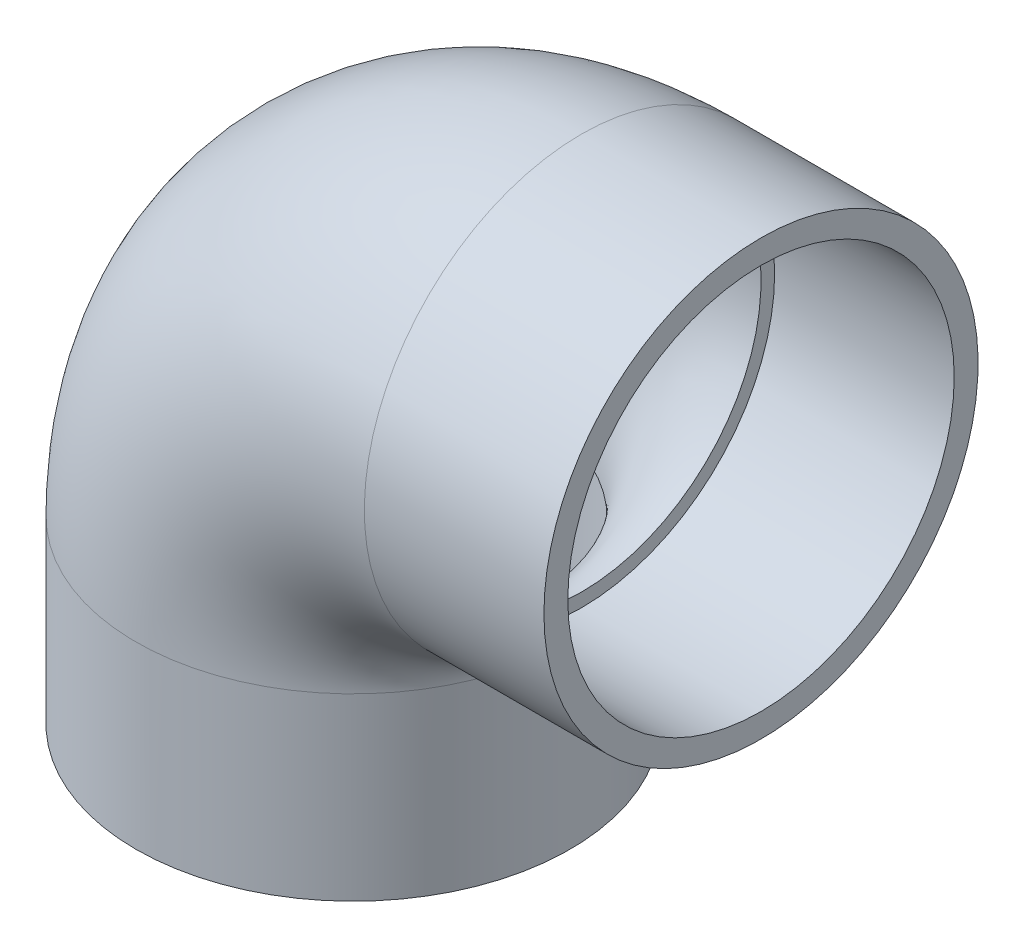
SolidWorks part; units mm, degrees
ref_plane "Alzado" through (0, 0, 0) normal (0, 0, 1) x (1, 0, 0)
ref_plane "Planta" through (0, 0, 0) normal (0, 1, 0) x (1, 0, 0)
ref_plane "Vista lateral" through (0, 0, 0) normal (1, 0, 0) x (0, 0, -1)
sketch "Croquis3" plane through (0, 0, 0) normal (0, 0, 1) x (1, 0, 0)
  line L0 (0, 79) -> (0, 0)
  line L1 (100.5, 179.5) -> (179.5, 179.5)
  arc A0 (0, 79) -> (100.5, 179.5) centre (100.5, 79) cw
  dimension "D1" = 100.5
  dimension "D2" = 79
  dimension "D3" = 79
sketch "Croquis4" plane through (0, 0, 0) normal (0, 1, 0) x (1, 0, 0)
  circle A0 centre (0, 0) radius 95.5
  circle A1 centre (0, 0) radius 79
  dimension "D1" = 191
  dimension "D2" = 158
sweep "Barrer5" add profiles "Croquis4" path "Croquis3"
sketch "Croquis6" plane through (0, 0, 0) normal (0, -1, 0) x (1, 0, 0)
  circle A0 centre (0, 0) radius 79
  circle A1 centre (0, 0) radius 85
  dimension "D1" = 158
  dimension "D2" = 170
extrude "Cortar-Extruir1" cut sketch "Croquis6" against normal blind 79
sketch "Croquis7" plane through (179.5, 0, 0) normal (1, 0, 0) x (0, 0, -1)
  circle A0 centre (0, 179.5) radius 79
  circle A1 centre (0, 179.5) radius 85
  dimension "D1" = 158
  dimension "D2" = 170
extrude "Cortar-Extruir2" cut sketch "Croquis7" against normal blind 79
